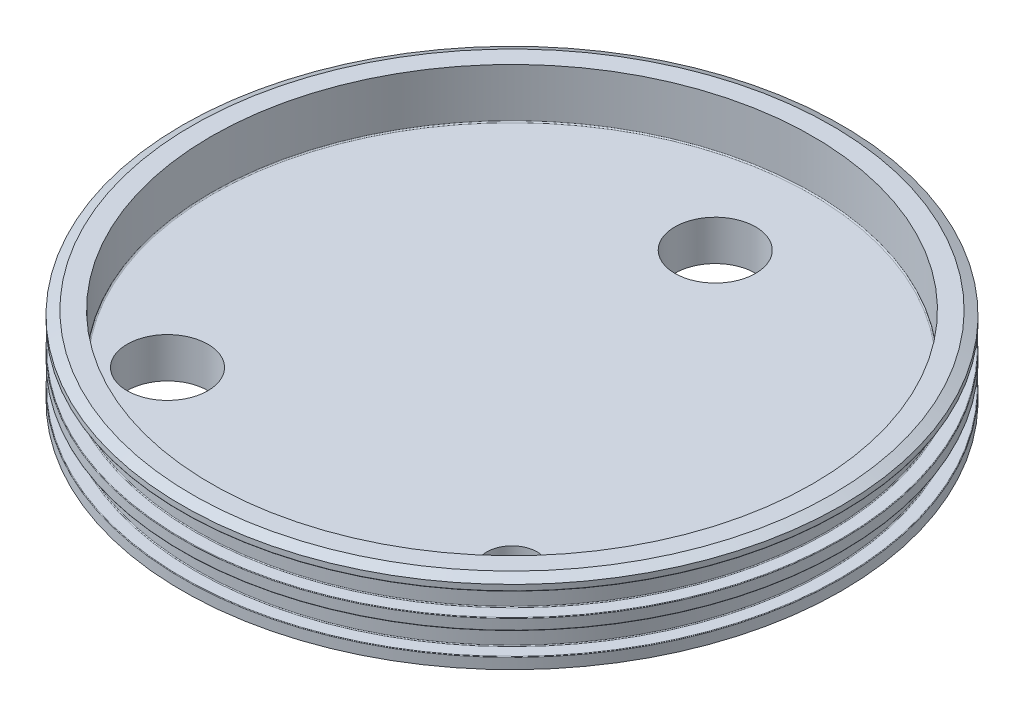
SolidWorks part; units mm, degrees
material "6061-T6 (SS)"
ref_plane "Front Plane" through (0, 0, 0) normal (0, 0, 1) x (1, 0, 0)
ref_plane "Top Plane" through (0, 0, 0) normal (0, 1, 0) x (1, 0, 0)
ref_plane "Right Plane" through (0, 0, 0) normal (1, 0, 0) x (0, 0, -1)
sketch "Sketch1" plane through (0, 0, 0) normal (0, 0, 1) x (1, 0, 0)
  line L0 (0, 48.1922) -> (0, -25.6743) construction
  line L1 (0, 0) -> (72.898, 0)
  line L2 (72.898, 0) -> (72.898, 2.4638)
  line L3 (72.898, 2.4638) -> (69.977, 2.4638)
  line L4 (69.977, 2.4638) -> (69.977, 7.4422)
  line L5 (69.977, 7.4422) -> (72.898, 7.4422)
  line L6 (72.898, 7.4422) -> (72.898, 9.906)
  line L7 (72.898, 9.906) -> (69.977, 9.906)
  line L8 (66.548, 17.3482) -> (66.548, 6.35)
  line L9 (66.548, 6.35) -> (0, 6.35)
  line L10 (0, 6.35) -> (0, 0)
  line L11 (69.977, 9.906) -> (69.977, 14.986)
  line L12 (69.977, 14.986) -> (72.898, 14.986)
  line L13 (72.898, 14.986) -> (72.898, 17.3482)
  line L14 (72.898, 17.3482) -> (66.548, 17.3482)
  dimension "D1" = 145.796
  dimension "D2" = 4.9784
  dimension "D3" = 2.921
  dimension "D4" = 9.906
  dimension "D5" = 6.35
  dimension "D6" = 6.35
  dimension "D7" = 5.08
  dimension "D8" = 9.906
revolve "Revolve1" add sketch "Sketch1" angle 360 about L0
sketch "Sketch6" plane through (0, 0, 0) normal (0, -1, 0) x (1, 0, 0)
  circle A0 centre (0, 0) radius 66.04
  dimension "D1" = 132.08
extrude "Boss-Extrude1" add sketch "Sketch6" along normal blind 2.54
fillet "CNC ID Fillet" radius 0.1778 5 edges at (-69.977, 7.4422, 0) (-69.977, 2.4638, 0) (66.04, 0, 0) (-69.977, 14.986, 0) (-69.977, 9.906, 0)
fillet "CNC OD Fillet" radius 0.127 5 edges at (-72.898, 7.4422, 0) (-72.898, 2.4638, 0) (-72.898, 9.906, 0) (-72.898, 14.986, 0) (66.04, -2.54, 0)
chamfer "CNC Chamfers" distance 1.016 angle 65 1 edges at (-72.898, 17.3482, 0)
fillet "CNC Bore Fillet" radius 0.254 1 edges at (-66.548, 6.35, 0)
hole_wizard "Pipe Tap Drill for 1/2 Tap - Fill Valve" positions "Sketch13" profile "Sketch14" hole size "1/2" standard "ANSI Inch" end condition through all
sketch "Sketch13" plane through (0, -2.54, 0) normal (0, -1, 0) x (-1, 0, 0)
  point P4 (0, 44.958)
  dimension "D1" = 44.958
sketch "Sketch14" plane through (0, -2.54, -44.958) normal (1, 0, 0) x (0, 0, -1)
  line L0 (0, 0) -> (0, 19.8882)
  line L1 (0, 19.8882) -> (8.9281, 19.8882)
  line L2 (8.9281, 19.8882) -> (8.9281, 0)
  line L5 (8.9281, 0) -> (0, 0)
  line L11 (0, -6.35) -> (0, 107.95) construction
  dimension "Thru Hole Dia." = 17.8562
  dimension "Thru Hole Depth" = 19.8882
hole_wizard "Pipe Tap Drill for 1/4 Tap - Solenoid Valve" positions "Sketch15" profile "Sketch16" hole size "1/4" standard "ANSI Inch" end condition through all
sketch "Sketch15" plane through (0, -2.54, 0) normal (0, -1, 0) x (-1, 0, 0)
  point P4 (-38.1, -38.1)
  point P11 (0, 0)
  point P12 (-28.9933, -34.36)
  dimension "D1" = 38.1
  dimension "D2" = 38.1
sketch "Sketch16" plane through (38.1, -2.54, 38.1) normal (1, 0, 0) x (0, 0, -1)
  line L0 (0, 0) -> (0, 19.8882)
  line L1 (0, 19.8882) -> (5.5626, 19.8882)
  line L2 (5.5626, 19.8882) -> (5.5626, 0)
  line L5 (5.5626, 0) -> (0, 0)
  line L11 (0, -6.35) -> (0, 107.95) construction
  dimension "Thru Hole Dia." = 11.1252
  dimension "Thru Hole Depth" = 19.8882
hole_wizard "Pipe Tap Drill for 1/2 Tap - Cryo Valve" positions "Sketch17" profile "Sketch18" hole size "1/2" standard "ANSI Inch" end condition through all
sketch "Sketch17" plane through (0, -2.54, 0) normal (0, -1, 0) x (-1, 0, 0)
  point P4 (38.1, -38.1)
  point P7 (0, 0)
  point P11 (0, 0)
  point P12 (0, 0)
  point P14 (0, 0)
  point P15 (39.1891, 34.5786)
  dimension "D1" = 38.1
  dimension "D2" = 38.1
sketch "Sketch18" plane through (-38.1, -2.54, 38.1) normal (1, 0, 0) x (0, 0, -1)
  line L0 (0, 0) -> (0, 19.8882)
  line L1 (0, 19.8882) -> (8.9281, 19.8882)
  line L2 (8.9281, 19.8882) -> (8.9281, 0)
  line L5 (8.9281, 0) -> (0, 0)
  line L11 (0, -6.35) -> (0, 107.95) construction
  dimension "Thru Hole Dia." = 17.8562
  dimension "Thru Hole Depth" = 19.8882
